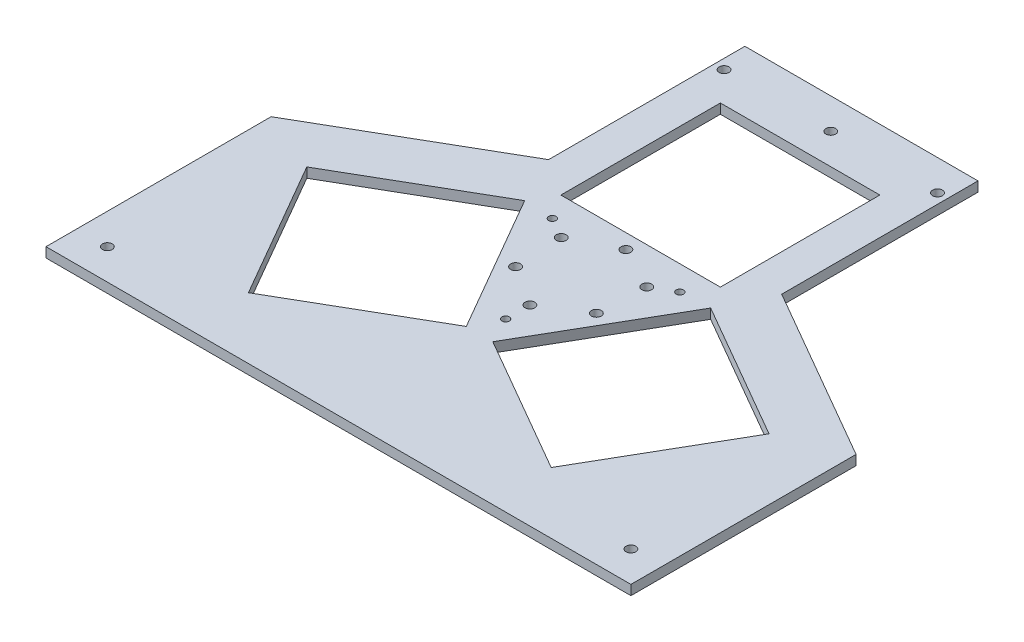
SolidWorks part; units mm, degrees
material "6061 合金"
ref_plane "Front" through (0, 0, 0) normal (0, 0, 1) x (1, 0, 0)
ref_plane "Top" through (0, 0, 0) normal (0, 1, 0) x (1, 0, 0)
ref_plane "Right" through (0, 0, 0) normal (1, 0, 0) x (0, 0, -1)
sketch "草图1" plane through (0, 0, 0) normal (0, 1, 0) x (1, 0, 0)
  line L0 (0, 0) -> (0, -188.4626) construction
  line L2 (119.1923, -98.1458) -> (119.1923, -6.3916)
  line L3 (47.5, 115) -> (-47.5, 115)
  line L4 (-119.1923, -98.1458) -> (-119.1923, -6.3916)
  line L5 (-119.1923, -85.6458) -> (119.1923, -85.6458) construction
  line L6 (-106.6923, -98.1458) -> (-106.6923, 0) construction
  line L7 (0, 19) -> (-16.4545, -9.5) construction
  line L8 (-16.4545, -9.5) -> (16.4545, -9.5) construction
  line L9 (16.4545, -9.5) -> (0, 19) construction
  line L10 (0, -30) -> (25.9808, 15) construction
  line L11 (25.9808, 15) -> (-25.9808, 15) construction
  line L12 (-25.9808, 15) -> (0, -30) construction
  line L14 (-32.5, 90) -> (32.5, 90)
  line L15 (-32.5, 90) -> (-32.5, 25)
  line L16 (-32.5, 25) -> (32.5, 25)
  line L17 (32.5, 90) -> (32.5, 25)
  line L18 (-32.5, 90) -> (32.5, 25) construction
  line L19 (-32.5, 25) -> (32.5, 90) construction
  line L27 (37.9006, 15.6458) -> (5.4006, -40.6458)
  line L28 (61.6923, -73.1458) -> (5.4006, -40.6458)
  line L29 (94.1923, -16.8542) -> (37.9006, 15.6458)
  line L30 (94.1923, -16.8542) -> (61.6923, -73.1458)
  line L31 (-5.4006, -40.6458) -> (-37.9006, 15.6458)
  line L32 (-94.1923, -16.8542) -> (-37.9006, 15.6458)
  line L33 (-61.6923, -73.1458) -> (-5.4006, -40.6458)
  line L34 (-61.6923, -73.1458) -> (-94.1923, -16.8542)
  line L35 (-47.5, 115) -> (-47.5, 35)
  line L36 (-47.5, 35) -> (-119.1923, -6.3916)
  line L37 (47.5, 35) -> (119.1923, -6.3916)
  line L38 (47.5, 115) -> (47.5, 35)
  line L39 (-119.1923, -98.1458) -> (119.1923, -98.1458)
  line L40 (-47.5, 102.5) -> (47.5, 102.5) construction
  line L41 (0, 115) -> (0, 19) construction
  line L42 (106.6923, -98.1458) -> (106.6923, 0.8253) construction
  line L44 (0, -20.125) -> (17.4288, 10.0625) construction
  line L45 (17.4288, 10.0625) -> (-17.4288, 10.0625) construction
  line L46 (-17.4288, 10.0625) -> (0, -20.125) construction
  circle A0 centre (0, 0) radius 9.5 construction
  circle A4 centre (0, 0) radius 15 construction
  circle A8 centre (0, 19) radius 2
  circle A9 centre (25.9808, 15) radius 1.5
  circle A10 centre (16.4545, -9.5) radius 2
  circle A11 centre (0, -30) radius 1.5
  circle A12 centre (-16.4545, -9.5) radius 2
  circle A14 centre (-25.9808, 15) radius 1.5
  circle A15 centre (0, 0) radius 57.5 construction
  circle A16 centre (0, 102.5) radius 2
  circle A17 centre (-106.6923, -85.6458) radius 2
  circle A18 centre (106.6923, -85.6458) radius 2
  circle A19 centre (-43.5, 102.5) radius 2
  circle A20 centre (43.5, 102.5) radius 2
  circle A21 centre (0, 0) radius 20.125 construction
  circle A22 centre (-17.4288, 10.0625) radius 2
  circle A23 centre (17.4288, 10.0625) radius 2
  circle A24 centre (0, -20.125) radius 2
  point P0 (0, 0)
  point P25 (0, 57.5)
  point P37 (0, 0)
  dimension "D1" = 30
  dimension "D2" = 19
  dimension "D3" = 3
  dimension "D4" = 4
  dimension "D5" = 115
  dimension "D20" = 4
  dimension "D21" = 4
  dimension "D22" = 40.25
  dimension "D23" = 4
  dimension "D24" = 9.875
  dimension "D6" = 65
  dimension "D7" = 25
  dimension "D8" = 65
  dimension "D10" = 25
  dimension "D11" = 25
  dimension "D12" = 120
  dimension "D13" = 15
  dimension "D14" = 21.5609
  dimension "D15" = 80
  dimension "D16" = 12.5
  dimension "D17" = 12.5
  dimension "D18" = 12.5
  dimension "D19" = 12.5
  dimension "D9" = 3
extrude "凸台-拉伸1" add sketch "草图1" along normal blind 4
